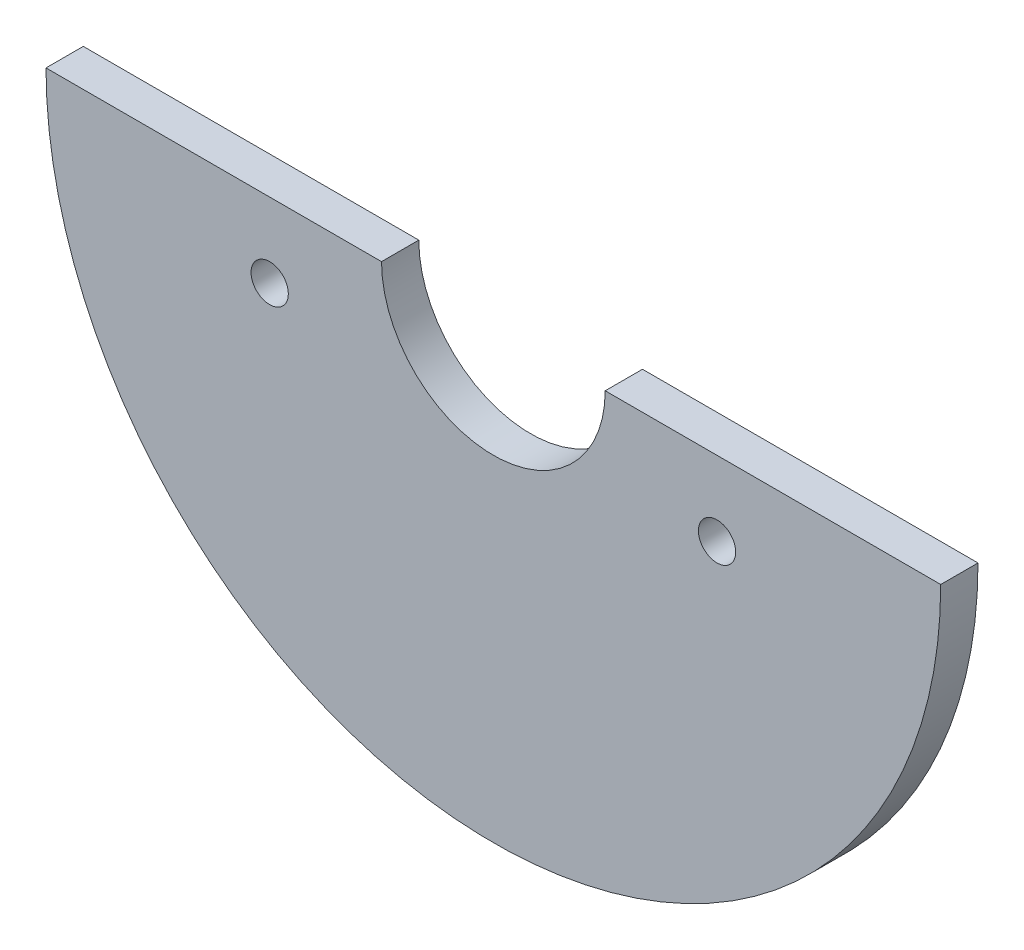
SolidWorks part; units mm, degrees
ref_plane "Front Plane" through (0, 0, 0) normal (0, 0, 1) x (1, 0, 0)
ref_plane "Top Plane" through (0, 0, 0) normal (0, 1, 0) x (1, 0, 0)
ref_plane "Right Plane" through (0, 0, 0) normal (1, 0, 0) x (0, 0, -1)
sketch "Sketch1" plane through (0, 0, 0) normal (0, 0, 1) x (1, 0, 0)
  line L0 (-60, 0) -> (-15, 0)
  line L1 (15, 0) -> (60, 0)
  circle A0 centre (0, 0) radius 60 construction
  arc A1 (-60, 0) -> (60, 0) centre (0, 0) ccw
  arc A2 (-15, 0) -> (15, 0) centre (0, 0) ccw
  circle A3 centre (30, -10) radius 2.5
  circle A4 centre (-30, -10) radius 2.5
  dimension "D1" = 120
  dimension "D2" = 15
  dimension "D4" = 10
  dimension "D5" = 5
  dimension "D6" = 5
  dimension "D7" = 10
  dimension "D8" = 30
  dimension "D3" = 30
extrude "Boss-Extrude1" add sketch "Sketch1" along normal blind 5
sketch "Sketch2" [suppressed] plane through (0, 0, 2) normal (0, 0, 1) x (1, 0, 0)
  line L0 (-12.5, 0) -> (-50, 0) construction
  line L1 (50, 0) -> (12.5, 0) construction
  line L2 (-31.8198, -31.8198) -> (0, 0) construction
  line L3 (0, 0) -> (31.8198, -31.8198) construction
  arc A0 (-45, 0) -> (45, 0) centre (0, 0) ccw construction
  arc A1 (-50, 0) -> (50, 0) centre (0, 0) ccw construction
  circle A2 centre (-31.8198, -31.8198) radius 1.5
  circle A3 centre (0, -45) radius 1.5
  circle A4 centre (31.8198, -31.8198) radius 1.5
  dimension "D1" = 45
  dimension "D2" = 3
  dimension "D5" = 3
  dimension "D3" = 45
  dimension "D4" = 45
extrude "Cut-Extrude1" [suppressed] cut sketch "Sketch2" against normal blind 2
